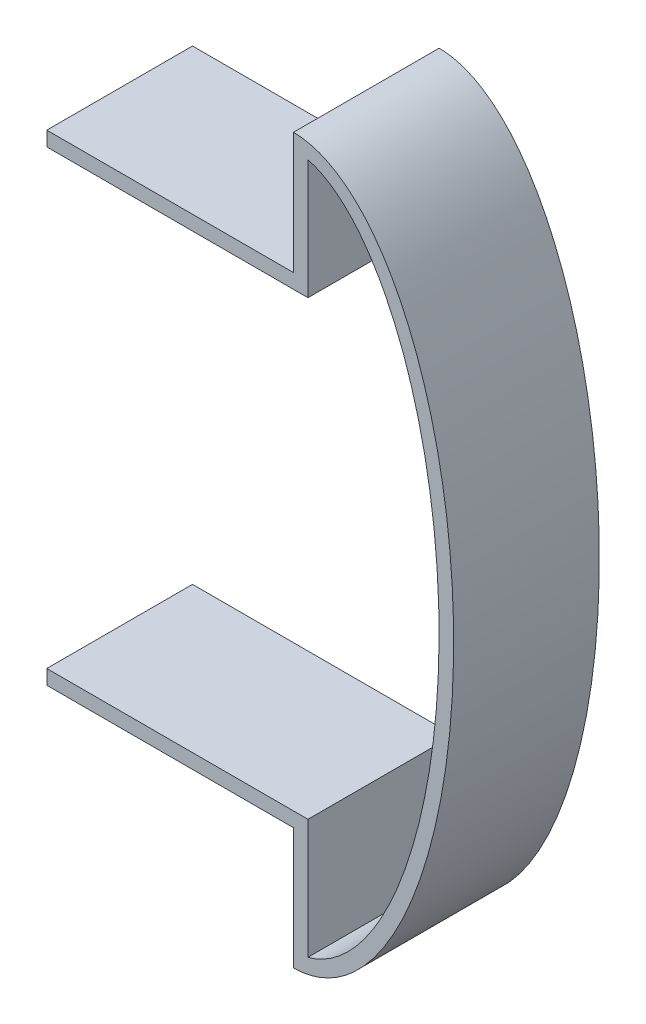
SolidWorks part; units mm, degrees
ref_plane "Front Plane" through (0, 0, 0) normal (0, 0, 1) x (1, 0, 0)
ref_plane "Top Plane" through (0, 0, 0) normal (0, 1, 0) x (1, 0, 0)
ref_plane "Right Plane" through (0, 0, 0) normal (1, 0, 0) x (0, 0, -1)
sketch "Sketch1" plane through (0, 0, 0) normal (0, 0, 1) x (1, 0, 0)
  line L3 (126.2212, 121) -> (180, 121)
  line L7 (180, 121) -> (180, 145.6127)
  line L8 (177, 0) -> (177, 25) construction
  line L9 (177, 25) -> (118, 25) construction
  line L10 (118, 124) -> (177, 124) construction
  line L11 (177, 124) -> (177, 149) construction
  line L20 (177, 0) -> (177, 25)
  line L21 (177, 25) -> (126.2212, 25)
  line L22 (126.2212, 124) -> (177, 124)
  line L23 (177, 124) -> (177, 149)
  line L37 (180, 3.3873) -> (180, 28)
  line L38 (180, 28) -> (126.2212, 28)
  line L39 (126.2212, 124) -> (126.2212, 121)
  line L40 (126.2212, 25) -> (126.2212, 28)
  circle A0 centre (192.5, 50.5) radius 2 construction
  circle A1 centre (192.5, 98.5) radius 2 construction
  circle A4 centre (192.5, 50.5) radius 2
  circle A5 centre (192.5, 98.5) radius 2
  ellipse E1 centre (177, 74.5) end of major axis (177, 149) minor radius 33 (177, 0) -> (177, 149) ccw construction
  ellipse E3 centre (177, 74.5) end of major axis (177, 149) minor radius 33 (177, 0) -> (177, 149) ccw
  spline S0 degree 1 poles (180, 3.3873) (180, 145.6127) knots 0 0 1 1 construction
  spline S1 degree 3 poles (180, 145.6127) (180.4105, 145.5067) (181.2094, 145.2584) (182.8503, 144.5777) (184.9209, 143.3851) (187.4286, 141.3778) (190.7421, 137.9293) (194.7232, 132.1978) (198.9591, 123.2786) (202.4483, 112.6486) (205.9097, 96.7054) (207.7269, 74.5) (205.9097, 52.2946) (202.4483, 36.3514) (198.9591, 25.7214) (194.7232, 16.8022) (190.7421, 11.0707) (187.4286, 7.6222) (184.9209, 5.6149) (182.8503, 4.4223) (181.2094, 3.7416) (180.4105, 3.4933) (180, 3.3873) knots 3.255477 3.255477 3.255477 3.255477 3.301005 3.346534 3.437591 3.528648 3.619705 3.801819 3.983933 4.166047 4.348161 4.712389 5.076617 5.258731 5.440845 5.622959 5.805073 5.89613 5.987187 6.078244 6.123773 6.169301 6.169301 6.169301 6.169301
  point P4 (0, 0)
  point P5 (0, 0)
  point P6 (0, 0)
  dimension "D1" = 3
extrude "Boss-Extrude1" add sketch "Sketch1" along normal blind 30 contours L23 E3 L20 L21 L40 L38 L37 S1 L7 L3 L39 L22
